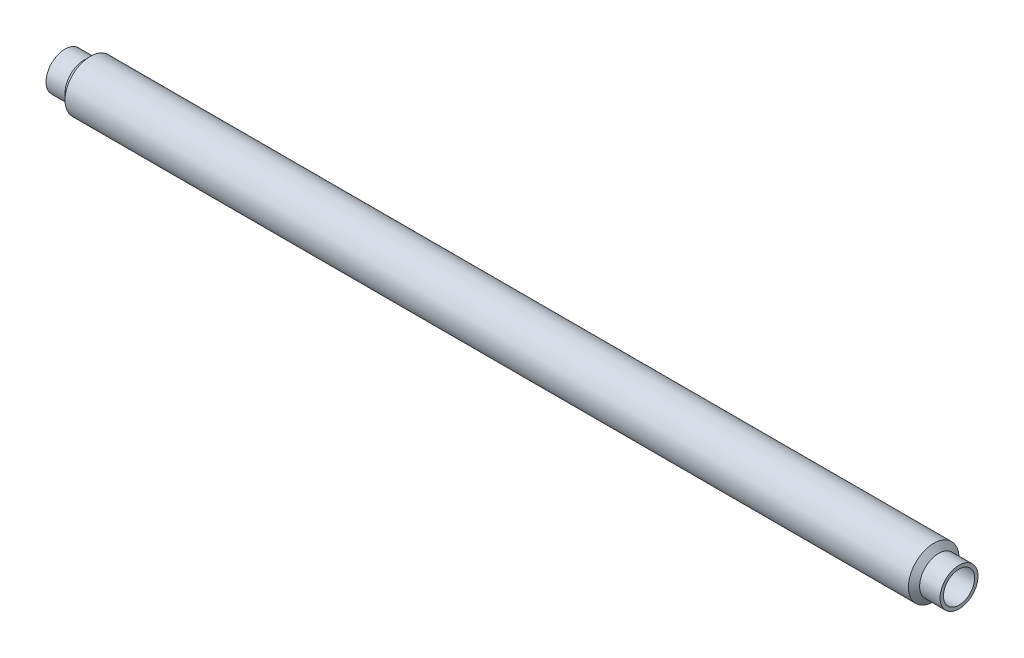
SolidWorks part; units mm, degrees
ref_plane "Front Plane" through (0, 0, 0) normal (0, 0, 1) x (1, 0, 0)
ref_plane "Top Plane" through (0, 0, 0) normal (0, 1, 0) x (1, 0, 0)
ref_plane "Right Plane" through (0, 0, 0) normal (1, 0, 0) x (0, 0, -1)
sketch "Sketch1" plane through (0, 0, 0) normal (1, 0, 0) x (0, 0, -1)
  circle A0 centre (0, 0) radius 150
  circle A1 centre (0, 0) radius 62.5
  dimension "D1" = 300
  dimension "D2" = 125
extrude "Boss-Extrude1" add sketch "Sketch1" along normal blind 5000
sketch "Sketch2" plane through (5000, 0, 0) normal (1, 0, 0) x (0, 0, -1)
  circle A0 centre (0, 0) radius 112.5
  circle A1 centre (0, 0) radius 92.5
  dimension "D1" = 225
  dimension "D2" = 185
extrude "Boss-Extrude2" add sketch "Sketch2" along normal blind 150 separate body
sketch "Sketch4" plane through (0, 0, 0) normal (0, 0, 1) x (1, 0, 0)
  line L3 (5000, 150) -> (5000, 112.5)
  line L4 (5128.6321, 0) -> (4589.2172, 0) construction
  line L6 (5000, 112.5) -> (5028.9502, 112.5)
  line L7 (5150, 112.5) -> (5000, 112.5) construction
  line L8 (5028.9502, 112.5) -> (5000, 150)
revolve "Revolve1" add sketch "Sketch4" angle 360 about L4
sketch "Sketch6" plane through (0, 0, 0) normal (-1, 0, 0) x (0, 0, 1)
  circle A0 centre (0, 0) radius 87.5
  circle A1 centre (0, 0) radius 112.5
  dimension "D1" = 175
  dimension "D2" = 225
extrude "Boss-Extrude3" add sketch "Sketch6" along normal blind 150 separate body
sketch "Sketch7" plane through (0, 0, 0) normal (0, 0, 1) x (1, 0, 0)
  line L0 (0, 0) -> (-301.92, 0) construction
  line L5 (0, 150) -> (0, 112.5)
  line L6 (0, 112.5) -> (-37.1196, 112.5)
  line L7 (0, 112.5) -> (-150, 112.5) construction
  line L8 (-37.1196, 112.5) -> (0, 150)
  point P5 (-37.1196, 112.5)
revolve "Revolve2" add sketch "Sketch7" angle 360 about L0
